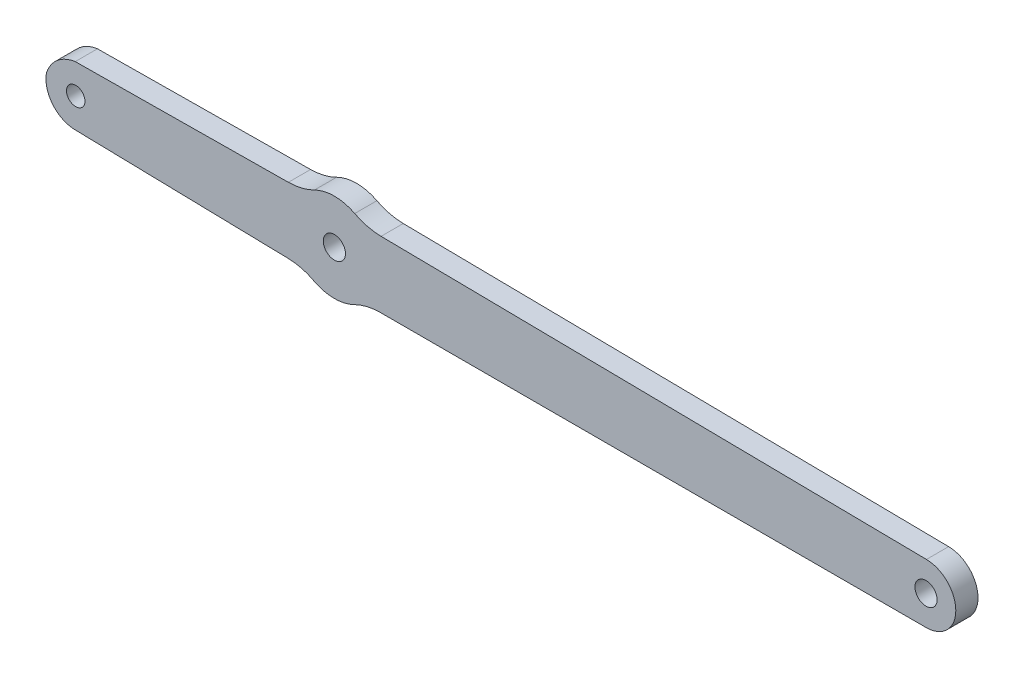
SolidWorks part; units mm, degrees
ref_plane "前基準面" through (0, 0, 0) normal (0, 0, 1) x (1, 0, 0)
ref_plane "上基準面" through (0, 0, 0) normal (0, 1, 0) x (1, 0, 0)
ref_plane "右基準面" through (0, 0, 0) normal (1, 0, 0) x (0, 0, -1)
sketch "草圖1" plane through (0, 0, 0) normal (0, 0, 1) x (1, 0, 0)
  line L0 (274.2993, 148.4231) -> (281.7994, 148.4236) construction
  line L1 (245.4005, 148.4213) -> (273.2993, 148.4231) construction
  line L2 (281.799, 156.4229) -> (208.06, 157.3882) construction
  line L3 (208.0015, 148.4189) -> (244.4005, 148.4212) construction
  line L4 (166.6587, 149.1735) -> (195.469, 148.522) construction
  line L5 (195.5272, 157.4483) -> (166.7108, 157.1723) construction
  line L6 (274.2993, 148.4231) -> (281.7994, 148.4236)
  line L7 (245.4005, 148.4213) -> (273.2993, 148.4231)
  line L8 (281.799, 156.4229) -> (208.06, 157.3882)
  line L9 (208.0015, 148.4189) -> (244.4005, 148.4212)
  line L10 (166.6587, 149.1735) -> (195.469, 148.522)
  line L11 (195.5272, 157.4483) -> (166.7108, 157.1723)
  line L12 (244.4005, 148.4212) -> (245.4005, 148.4213)
  line L13 (273.2993, 148.4231) -> (274.2993, 148.4231)
  arc A0 (281.7994, 148.4236) -> (281.799, 156.4229) centre (281.7729, 152.4232) ccw construction
  circle A1 centre (281.7466, 152.4233) radius 1.5 construction
  arc A2 (204.4982, 158.2772) -> (208.06, 157.3882) centre (208.1649, 165.3881) ccw construction
  arc A3 (195.5272, 157.4483) -> (199.0493, 158.3031) centre (195.4465, 165.4646) ccw construction
  arc A4 (204.4982, 158.2772) -> (199.0493, 158.3031) centre (201.7483, 152.9448) ccw construction
  circle A5 centre (201.7484, 152.9445) radius 1.5 construction
  arc A6 (208.0015, 148.4189) -> (204.4285, 147.5764) centre (208.0022, 140.4182) ccw construction
  arc A7 (198.9797, 147.6214) -> (204.4285, 147.5764) centre (201.7483, 152.9445) ccw construction
  arc A8 (198.9797, 147.6214) -> (195.469, 148.522) centre (195.4045, 140.9776) ccw construction
  circle A9 centre (166.7753, 153.1793) radius 1.25 construction
  arc A10 (162.8149, 153.8955) -> (166.6587, 149.1735) centre (166.7491, 153.1725) ccw construction
  arc A11 (166.7108, 157.1723) -> (162.8149, 153.8955) centre (167.3488, 152.4594) ccw construction
  arc A12 (281.7994, 148.4236) -> (281.799, 156.4229) centre (281.7729, 152.4232) ccw
  circle A13 centre (281.7466, 152.4233) radius 1.5
  arc A14 (204.4982, 158.2772) -> (208.06, 157.3882) centre (208.1649, 165.3881) ccw
  arc A15 (195.5272, 157.4483) -> (199.0493, 158.3031) centre (195.4465, 165.4646) ccw
  arc A16 (204.4982, 158.2772) -> (199.0493, 158.3031) centre (201.7483, 152.9448) ccw
  circle A17 centre (201.7484, 152.9445) radius 1.5
  arc A18 (208.0015, 148.4189) -> (204.4285, 147.5764) centre (208.0022, 140.4182) ccw
  arc A19 (198.9797, 147.6214) -> (204.4285, 147.5764) centre (201.7483, 152.9445) ccw
  arc A20 (198.9797, 147.6214) -> (195.469, 148.522) centre (195.4045, 140.9776) ccw
  circle A21 centre (166.7753, 153.1793) radius 1.25
  arc A22 (162.8149, 153.8955) -> (166.6587, 149.1735) centre (166.7491, 153.1725) ccw
  arc A23 (166.7108, 157.1723) -> (162.8149, 153.8955) centre (167.3488, 152.4594) ccw
  point P0 (199.0493, 158.3031)
extrude "填料-伸長1" add sketch "草圖1" along normal blind 3
